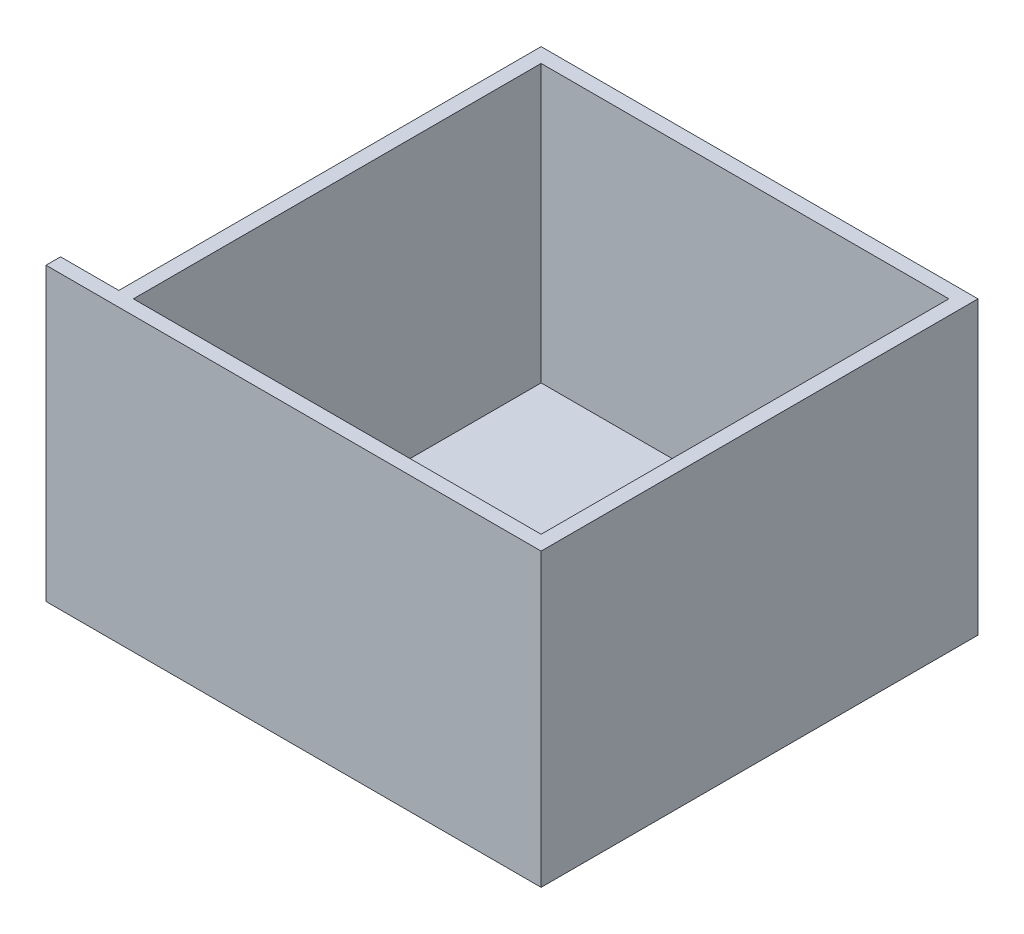
SolidWorks part; units mm, degrees
ref_plane "Front Plane" through (0, 0, 0) normal (0, 0, 1) x (1, 0, 0)
ref_plane "Top Plane" through (0, 0, 0) normal (0, 1, 0) x (1, 0, 0)
ref_plane "Right Plane" through (0, 0, 0) normal (1, 0, 0) x (0, 0, -1)
sketch "Sketch1" plane through (0, 0, 0) normal (0, 1, 0) x (1, 0, 0)
  line L1 (7.5, 7.5) -> (-7.5, 7.5)
  line L2 (7.5, 7.5) -> (7.5, -7.5)
  line L3 (7.5, -7.5) -> (-7.5, -7.5)
  line L4 (-7.5, 7.5) -> (-7.5, -7.5)
  line L5 (7.5, 7.5) -> (-7.5, -7.5) construction
  line L6 (7.5, -7.5) -> (-7.5, 7.5) construction
  point P0 (0, 0)
  dimension "D1" = 15
  dimension "D2" = 15
extrude "Boss-Extrude1" add sketch "Sketch1" along normal blind 10
shell "Shell6" thickness 0.5
sketch "Sketch2" plane through (-7.5, 0, 0) normal (-1, 0, 0) x (0, 0, 1)
  line L0 (-7.5, 0) -> (7.5, 0)
  line L1 (7.5, 0) -> (7.5, 0.5)
  line L2 (7.5, 10) -> (7.5, 0) construction
  line L3 (6.9, 0.5) -> (6.6801, 0.5)
  line L4 (-7.5, 10) -> (-7.5, 0) construction
  line L5 (-7.5, 0.5) -> (-7.5, 0)
  line L6 (-7.5, 0.5) -> (-7.1546, 1.3094)
  line L7 (-7.1546, 1.3094) -> (-6.8199, 0.5)
  line L8 (-6.6, 0.5) -> (-6.2546, 1.3094)
  line L9 (-6.2546, 1.3094) -> (-5.9199, 0.5)
  line L10 (-5.7, 0.5) -> (-5.3546, 1.3094)
  line L11 (-5.3546, 1.3094) -> (-5.0199, 0.5)
  line L12 (-4.8, 0.5) -> (-4.4546, 1.3094)
  line L13 (-4.4546, 1.3094) -> (-4.1199, 0.5)
  line L14 (-3.9, 0.5) -> (-3.5546, 1.3094)
  line L15 (-3.5546, 1.3094) -> (-3.2199, 0.5)
  line L16 (-3, 0.5) -> (-2.6546, 1.3094)
  line L17 (-2.6546, 1.3094) -> (-2.3199, 0.5)
  line L18 (-2.1, 0.5) -> (-1.7546, 1.3094)
  line L19 (-1.7546, 1.3094) -> (-1.4199, 0.5)
  line L20 (-1.2, 0.5) -> (-0.8546, 1.3094)
  line L21 (-0.8546, 1.3094) -> (-0.5199, 0.5)
  line L22 (-0.3, 0.5) -> (0.0454, 1.3094)
  line L23 (0.0454, 1.3094) -> (0.3801, 0.5)
  line L24 (0.6, 0.5) -> (0.9454, 1.3094)
  line L25 (0.9454, 1.3094) -> (1.2801, 0.5)
  line L26 (1.5, 0.5) -> (1.8454, 1.3094)
  line L27 (1.8454, 1.3094) -> (2.1801, 0.5)
  line L28 (2.4, 0.5) -> (2.7454, 1.3094)
  line L29 (2.7454, 1.3094) -> (3.0801, 0.5)
  line L30 (3.3, 0.5) -> (3.6454, 1.3094)
  line L31 (3.6454, 1.3094) -> (3.9801, 0.5)
  line L32 (4.2, 0.5) -> (4.5454, 1.3094)
  line L33 (4.5454, 1.3094) -> (4.8801, 0.5)
  line L34 (5.1, 0.5) -> (5.4454, 1.3094)
  line L35 (5.4454, 1.3094) -> (5.7801, 0.5)
  line L36 (6, 0.5) -> (6.3454, 1.3094)
  line L37 (6.3454, 1.3094) -> (6.6801, 0.5)
  line L38 (6.9, 0.5) -> (7.2454, 1.3094) construction
  line L39 (7.2454, 1.3094) -> (7.5, 0.6937) construction
  line L40 (-6.8199, 0.5) -> (-7.5, 0.5) construction
  line L41 (-6.6, 0.5) -> (-6.8199, 0.5)
  line L42 (-5.9199, 0.5) -> (-6.6, 0.5) construction
  line L43 (-5.7, 0.5) -> (-5.9199, 0.5)
  line L44 (-5.0199, 0.5) -> (-5.7, 0.5) construction
  line L45 (-4.8, 0.5) -> (-5.0199, 0.5)
  line L46 (-4.1199, 0.5) -> (-4.8, 0.5) construction
  line L47 (-3.9, 0.5) -> (-4.1199, 0.5)
  line L48 (-3.2199, 0.5) -> (-3.9, 0.5) construction
  line L49 (-3, 0.5) -> (-3.2199, 0.5)
  line L50 (-2.3199, 0.5) -> (-3, 0.5) construction
  line L51 (-2.1, 0.5) -> (-2.3199, 0.5)
  line L52 (-1.4199, 0.5) -> (-2.1, 0.5) construction
  line L53 (-1.2, 0.5) -> (-1.4199, 0.5)
  line L54 (-0.5199, 0.5) -> (-1.2, 0.5) construction
  line L55 (-0.3, 0.5) -> (-0.5199, 0.5)
  line L56 (0.3801, 0.5) -> (-0.3, 0.5) construction
  line L57 (0.6, 0.5) -> (0.3801, 0.5)
  line L58 (1.2801, 0.5) -> (0.6, 0.5) construction
  line L59 (1.5, 0.5) -> (1.2801, 0.5)
  line L60 (2.1801, 0.5) -> (1.5, 0.5) construction
  line L61 (2.4, 0.5) -> (2.1801, 0.5)
  line L62 (3.0801, 0.5) -> (2.4, 0.5) construction
  line L63 (3.3, 0.5) -> (3.0801, 0.5)
  line L64 (3.9801, 0.5) -> (3.3, 0.5) construction
  line L65 (4.2, 0.5) -> (3.9801, 0.5)
  line L66 (4.8801, 0.5) -> (4.2, 0.5) construction
  line L67 (5.1, 0.5) -> (4.8801, 0.5)
  line L68 (5.7801, 0.5) -> (5.1, 0.5) construction
  line L69 (6, 0.5) -> (5.7801, 0.5)
  line L70 (6.6801, 0.5) -> (6, 0.5) construction
  line L71 (7.5, 0.6937) -> (7.5, 0.5)
  line L72 (7.5, 0.5) -> (6.9, 0.5) construction
  line L73 (6.9, 0.5) -> (7, 10)
  line L74 (7, 10) -> (7.5, 10)
  line L75 (7.5, 10) -> (7.5, 0.5)
  point P13 (0, 0)
  dimension "D1" = 0.5
  dimension "D2" = 0.8759
  dimension "D3" = 0.88
  dimension "D4" = 0.8094
  dimension "D5" = 17
extrude "Boss-Extrude3" add sketch "Sketch2" along normal blind 2 contours L1 L0 L5 L6 L7 L41 L8 L9 L43 L10 L11 L45 L12 L13 L47 L14 L15 L49 L16 L17 L51 L18 L19 L53 L20 L21 L55 L22 L23 L57 L24 L25 L59 L26 L27 L61 L28 L29 L63 L30 L31 L65 L32 L33 L67 L34 L35 L69 L36 L37 L3 L73 L74 L75
